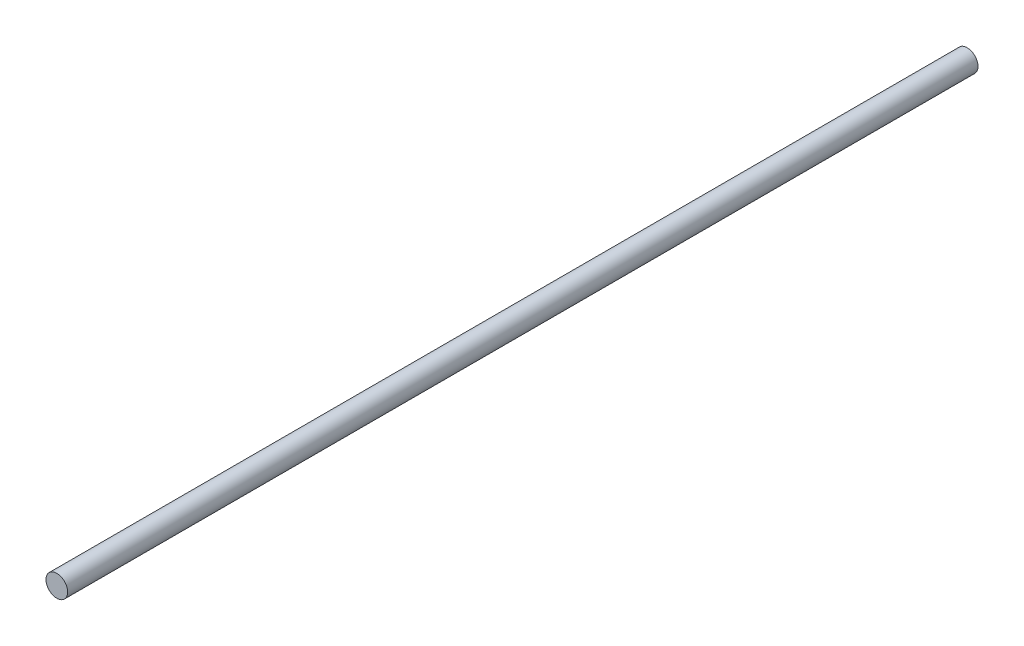
SolidWorks part; units mm, degrees
material "6061-T6 (SS)"
ref_plane "Front Plane" through (0, 0, 0) normal (0, 0, 1) x (1, 0, 0)
ref_plane "Top Plane" through (0, 0, 0) normal (0, 1, 0) x (1, 0, 0)
ref_plane "Right Plane" through (0, 0, 0) normal (1, 0, 0) x (0, 0, -1)
sketch "Sketch1" plane through (0, 0, 0) normal (0, 0, 1) x (1, 0, 0)
  circle A0 centre (0, 0) radius 4.445
  dimension "D1" = 8.89
extrude "Boss-Extrude1" add sketch "Sketch1" along normal blind 373.888
equation "\"d\"= .35in"
equation "\"A\"= pi * \"d\" ^ 2 / 4"
equation "\"L\"= .009 * \"A\" * 8500000 / 500"
